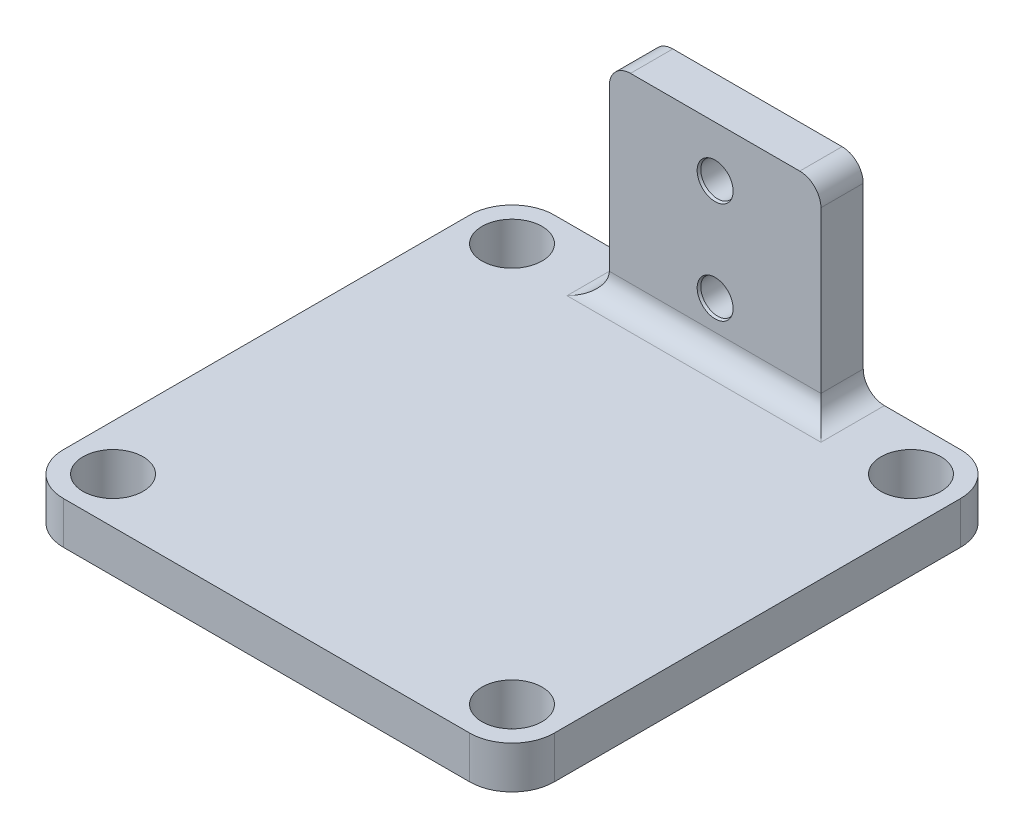
SolidWorks part; units mm, degrees
ref_plane "Front Plane" through (0, 0, 0) normal (0, 0, 1) x (1, 0, 0)
ref_plane "Top Plane" through (0, 0, 0) normal (0, 1, 0) x (1, 0, 0)
ref_plane "Right Plane" through (0, 0, 0) normal (1, 0, 0) x (0, 0, -1)
sketch "Sketch1" plane through (0, 0, 0) normal (0, 1, 0) x (1, 0, 0)
  line L0 (-23.57, 0) -> (23.57, 0) construction
  line L1 (-29, -29) -> (29, -29)
  line L2 (-29, -29) -> (-29, 29)
  line L3 (-29, 29) -> (29, 29)
  line L4 (29, -29) -> (29, 29)
  line L5 (-29, -29) -> (29, 29) construction
  line L6 (-29, 29) -> (29, -29) construction
  line L7 (-23.57, -29) -> (-23.57, -23.57) construction
  line L8 (-23.57, -23.57) -> (-29, -23.57) construction
  line L9 (0, -29) -> (0, 29) construction
  circle A0 centre (-23.57, -23.57) radius 2.55 construction
  circle A1 centre (23.57, -23.57) radius 2.55 construction
  circle A2 centre (23.57, 23.57) radius 2.55 construction
  circle A3 centre (-23.57, 23.57) radius 2.55 construction
  circle A4 centre (-23.57, 23.57) radius 3.55
  circle A5 centre (23.57, 23.57) radius 3.55
  circle A6 centre (23.57, -23.57) radius 3.55
  circle A7 centre (-23.57, -23.57) radius 3.55
  point P0 (0, 0)
  point P9 (0, 0)
  dimension "D3" = 5.1
  dimension "D4" = 7.1
  dimension "D1" = 58
  dimension "D2" = 47.14
extrude "Boss-Extrude1" add sketch "Sketch1" along normal blind 5
fillet "Fillet1" radius 5 4 edges at (29, 2.5, -29) (-29, 2.5, -29) (29, 2.5, 29) (-29, 2.5, 29)
sketch "Sketch5" plane through (0, 0, 0) normal (0, 0, 1) x (1, 0, 0)
  line L0 (0, 5) -> (0, 29) construction
  line L1 (-24, 5) -> (24, 5) construction
  line L3 (-12.5, 29) -> (12.5, 29)
  line L4 (12.5, 29) -> (12.5, 5)
  line L5 (12.5, 5) -> (-12.5, 5)
  line L7 (-12.5, 29) -> (-12.5, 5)
  dimension "D1" = 24
  dimension "D2" = 12.5
extrude "Boss-Extrude2" add sketch "Sketch5" along normal blind 5 from surface at -29 starting at face at (0, 2.5, -29)
sketch "Sketch6" plane through (0, 0, -24) normal (0, 0, 1) x (1, 0, 0)
  line L0 (0, 29) -> (0, 23) construction
  line L1 (12.5, 29) -> (-12.5, 29) construction
  line L2 (0, 5) -> (0, 11) construction
  line L3 (-12.5, 5) -> (12.5, 5) construction
  point P1 (0, 23)
  point P6 (0, 11)
  dimension "D1" = 6
hole_wizard "Ø4.0 (4) Diameter Hole1" positions "Sketch6" profile "Sketch7" hole size "Ø4.0" standard "ANSI Metric" end condition up to next
sketch "Sketch7" plane through (0, 11, -24) normal (1, 0, 0) x (0, -1, 0)
  line L0 (0, 0) -> (0, 5)
  line L1 (0, 5) -> (2, 5)
  line L2 (2, 5) -> (2, 0.3018)
  line L3 (2, 0.3018) -> (2.125, 0)
  line L5 (2.125, 0) -> (0, 0)
  line L6 (-2, 0.3018) -> (-2.125, 0) construction
  line L11 (0, -6.35) -> (0, 107.95) construction
  dimension "Thru Hole Dia." = 4
  dimension "Thru Hole Depth" = 5
  dimension "Near C'Sink Dia." = 4.25
  dimension "Near C'Sink Angle" = 45
fillet "Fillet2" radius 2.5 5 edges at (12.5, 5, -26.5) (-12.5, 5, -26.5) (12.5, 29, -26.5) (-12.5, 29, -26.5) (0, 5, -24)
